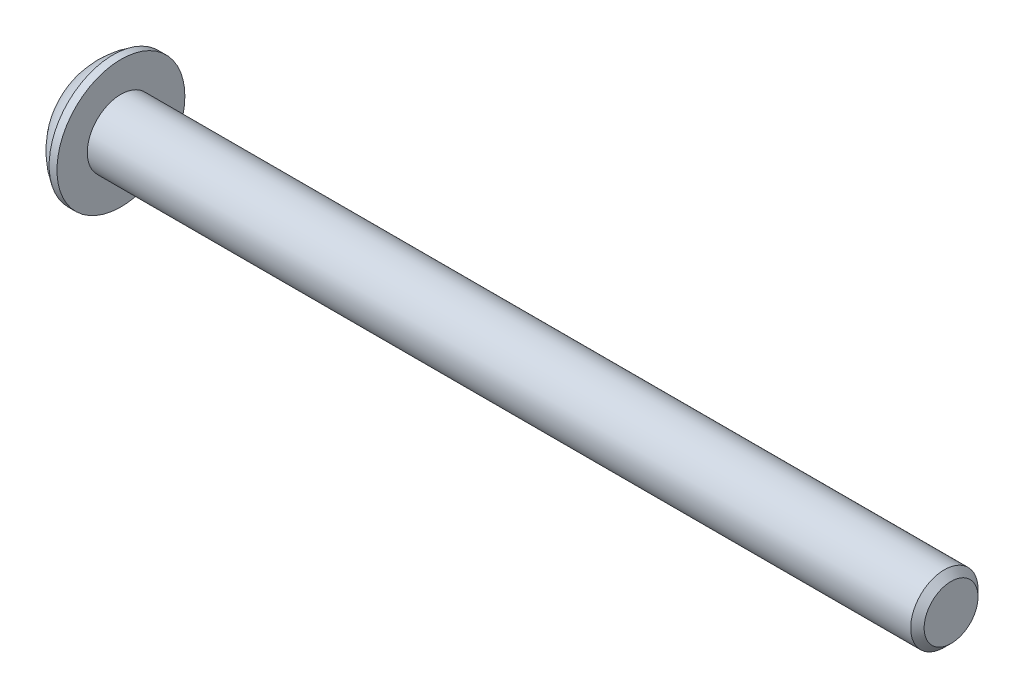
SolidWorks part; units mm, degrees
ref_plane "Front Plane" through (0, 0, 0) normal (0, 0, 1) x (1, 0, 0)
ref_plane "Top Plane" through (0, 0, 0) normal (0, 1, 0) x (1, 0, 0)
ref_plane "Right Plane" through (0, 0, 0) normal (1, 0, 0) x (0, 0, -1)
sketch "Sketch2" plane through (0, 0, 0) normal (0, 0, 1) x (1, 0, 0)
  line L0 (-18.5, 0) -> (18.5, 0) construction
  line L1 (18.5, 0) -> (-18.5, 0)
  line L3 (18.5, 0) -> (18.5, 1.5)
  line L4 (18.5, 1.5) -> (-18.5, 1.5)
  line L6 (0, 1.5) -> (0, 0) construction
  line L7 (18.5, 0) -> (-18.5, 0) construction
  line L8 (-18.5, 0) -> (-20.15, 0)
  line L9 (-20.15, 0) -> (-20.15, 1.43)
  line L10 (-18.85, 2.85) -> (-18.5, 2.85)
  line L11 (-18.5, 2.85) -> (-18.5, 1.5)
  arc A1 (-20.15, 1.43) -> (-18.85, 2.85) centre (-17.1333, -0.0267) cw
  point P3 (0, 0)
  point P9 (0, 0)
  point P11 (0, 0)
  point P13 (17.7911, 0)
  point P14 (-17.1333, 0)
  point P15 (0, 0)
  point P16 (0, 0)
  dimension "D2" = 0.35
  dimension "D3" = 1.65
  dimension "D5" = 3.35
  dimension "D1" = 37
  dimension "D4" = 2.85
  dimension "D6" = 1.43
revolve "Revolve2" add sketch "Sketch2" angle 360 about L1
chamfer "Chamfer1" distance 0.3 angle 45 1 edges at (18.5, 0, -1.5)
sketch "Sketch3" plane through (-20.15, 0, 0) normal (-1, 0, 0) x (0, 0, 1)
  line L7 (-1, 0.5774) -> (-1, -0.5774)
  line L8 (-1, -0.5774) -> (0, -1.1547)
  line L9 (0, -1.1547) -> (1, -0.5774)
  line L10 (1, -0.5774) -> (1, 0.5774)
  line L11 (1, 0.5774) -> (0, 1.1547)
  line L12 (0, 1.1547) -> (-1, 0.5774)
  circle A0 centre (0, 0) radius 1 construction
  point P1 (0, 0)
  point P9 (0, 0)
  dimension "D1" = 2
extrude "Cut-Extrude1" cut sketch "Sketch3" against normal blind 1
